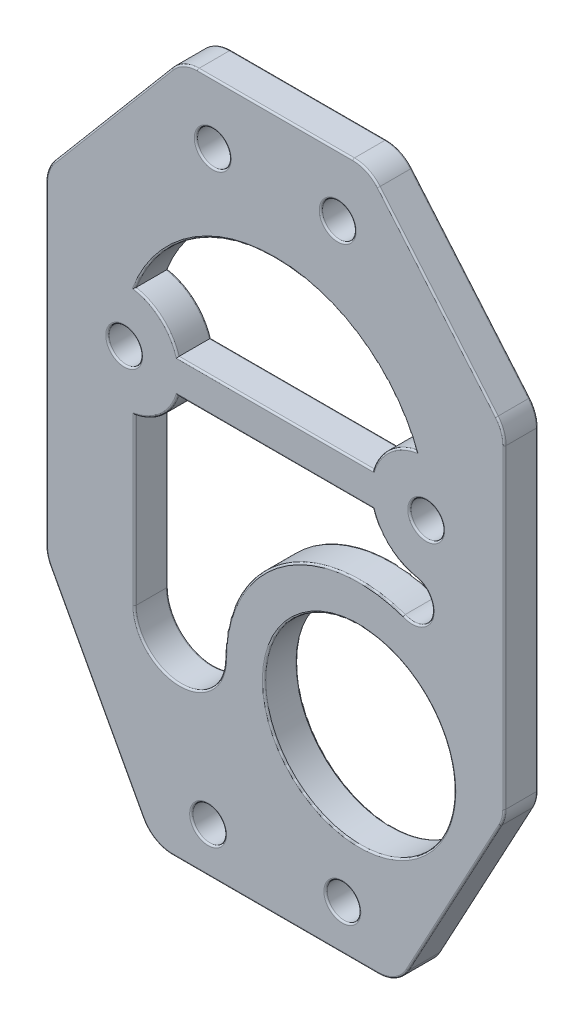
SolidWorks part; units mm, degrees
ref_plane "Front Plane" through (0, 0, 0) normal (0, 0, 1) x (1, 0, 0)
ref_plane "Top Plane" through (0, 0, 0) normal (0, 1, 0) x (1, 0, 0)
ref_plane "Right Plane" through (0, 0, 0) normal (1, 0, 0) x (0, 0, -1)
sketch "Sketch1" plane through (0, 0, 0) normal (0, 0, 1) x (1, 0, 0)
  line L0 (0, 0) -> (0, 62) construction
  line L1 (11, 0) -> (-11, 0)
  line L2 (-11, 0) -> (-20.5, 17.5997)
  line L3 (-20.5, 17.5997) -> (-20.5, 47.5997)
  line L4 (-20.5, 47.5997) -> (-8.3364, 62)
  line L5 (-8.3364, 62) -> (8.3364, 62)
  line L6 (20.5, 47.5997) -> (8.3364, 62)
  line L7 (20.5, 17.5997) -> (20.5, 47.5997)
  line L8 (11, 0) -> (20.5, 17.5997)
  line L9 (13.5, 37.2997) -> (-13.5, 37.2997) construction
  line L10 (-8.7303, 38.7997) -> (8.7303, 38.7997)
  line L11 (8.7303, 35.7997) -> (-8.7303, 35.7997) construction
  line L12 (8.7303, 35.7997) -> (8.7303, 38.7997) construction
  line L13 (8.7303, 38.7997) -> (-8.7303, 38.7997) construction
  line L14 (-8.7303, 35.7997) -> (-8.7303, 38.7997) construction
  line L15 (8.7303, 35.7997) -> (-8.7303, 38.7997) construction
  line L16 (8.7303, 38.7997) -> (-8.7303, 35.7997) construction
  line L17 (-8.7303, 35.7997) -> (8.7303, 35.7997)
  line L18 (13.5, 37.2997) -> (11.4846, 28.9188) construction
  line L19 (-12.5741, 32.3862) -> (-12.5741, 17.5997)
  circle A0 centre (-5.5864, 56.5294) radius 1.5
  circle A1 centre (-13.5, 37.2997) radius 1.5
  circle A2 centre (-6, 4) radius 1.5
  circle A3 centre (5.5864, 56.5294) radius 1.5
  circle A4 centre (6, 4) radius 1.5
  circle A5 centre (13.5, 37.2997) radius 1.5
  circle A6 centre (7.5, 17.5997) radius 8.5
  circle A7 centre (13.5, 37.2997) radius 5 construction
  circle A8 centre (-13.5, 37.2997) radius 5 construction
  circle A9 centre (7.5, 17.5997) radius 12 construction
  arc A10 (-12.5741, 42.2132) -> (12.5741, 42.2132) centre (0, 37.2997) cw
  arc A11 (-12.5741, 42.2132) -> (-8.7303, 38.7997) centre (-13.5, 37.2997) cw
  arc A12 (8.7303, 38.7997) -> (12.5741, 42.2132) centre (13.5, 37.2997) cw
  arc A13 (-8.7303, 35.7997) -> (-12.5741, 32.3862) centre (-13.5, 37.2997) cw
  arc A14 (8.7303, 35.7997) -> (12.5741, 32.3862) centre (13.5, 37.2997) ccw
  arc A15 (12.5741, 32.3862) -> (11.4846, 28.9188) centre (12.2352, 30.5879) cw
  arc A16 (11.4846, 28.9188) -> (-4.5, 17.5997) centre (7.5, 17.5997) ccw
  arc A17 (-12.5741, 17.5997) -> (-4.5, 17.5997) centre (-8.537, 17.5997) ccw
  dimension "D2" = 3
  dimension "D3" = 6
  dimension "D10" = 2.75
  dimension "D14" = 17
  dimension "D19" = 13.5
  dimension "D21" = 1.83
  dimension "D1" = 62
  dimension "D4" = 4
  dimension "D5" = 11
  dimension "D6" = 20
  dimension "D7" = 30
  dimension "D8" = 7
  dimension "D9" = 10.3
  dimension "D11" = 5.4706
  dimension "D12" = 18.85
  dimension "D13" = 20.5
  dimension "D15" = 13
  dimension "D20" = 3
  dimension "D16" = 3.5
  dimension "D17" = 3.5
  dimension "D18" = 3.5
extrude "Boss-Extrude1" add sketch "Sketch1" along normal mid plane 3
fillet "Fillet1" radius 3 8 edges at (-11, 0, 0) (-20.5, 17.5997, 0) (-20.5, 47.5997, 0) (-8.3364, 62, 0) (8.3364, 62, 0) (20.5, 47.5997, 0) (20.5, 17.5997, 0) (11, 0, 0)
fillet "Fillet2" radius 0.15 68 edges at (0.5652, 27.393, -1.5) (-8.537, 13.5627, -1.5) (-12.5741, 24.993, -1.5) (-10.1799, 33.5611, -1.5) (0, 35.7997, -1.5) (10.1799, 33.5611, -1.5) (13.981, 30.0393, -1.5) (16, 17.5997, -1.5) (4.5, 4, -1.5) (10.1799, 41.0383, -1.5) (0, 38.7997, -1.5) (-10.1799, 41.0383, -1.5) (0, 50.7997, -1.5) (-4.5, 4, -1.5) (-4.0864, 56.5294, -1.5) (10.7472, 0.4237, -1.5) (15.9951, 9.2539, -1.5) (20.4086, 17.6228, -1.5) (20.5, 32.43, -1.5) (20.3174, 47.5329, -1.5) (14.5135, 54.687, -1.5) (8.2068, 61.721, -1.5) (0, 62, -1.5) (-8.2068, 61.721, -1.5) (-14.5135, 54.687, -1.5) (-20.3174, 47.5329, -1.5) (-20.5, 32.43, -1.5) (-20.4086, 17.6228, -1.5) (-15.9951, 9.2539, -1.5) (-10.7472, 0.4237, -1.5) (0, 0, -1.5) (-12, 37.2997, -1.5) (4.0864, 56.5294, -1.5) (12, 37.2997, -1.5) (0, 35.7997, 1.5) (-10.1799, 33.5611, 1.5) (-12.5741, 24.993, 1.5) (-8.537, 13.5627, 1.5) (0.5652, 27.393, 1.5) (13.981, 30.0393, 1.5) (10.1799, 33.5611, 1.5) (-4.5, 4, 1.5) (-12, 37.2997, 1.5) (-4.0864, 56.5294, 1.5) (-20.4086, 17.6228, 1.5) (-20.5, 32.43, 1.5) (-20.3174, 47.5329, 1.5) (-14.5135, 54.687, 1.5) (-8.2068, 61.721, 1.5) (0, 62, 1.5) (8.2068, 61.721, 1.5) (14.5135, 54.687, 1.5) (20.3174, 47.5329, 1.5) (20.5, 32.43, 1.5) (20.4086, 17.6228, 1.5) (15.9951, 9.2539, 1.5) (10.7472, 0.4237, 1.5) (0, 0, 1.5) (-10.7472, 0.4237, 1.5) (-15.9951, 9.2539, 1.5) (0, 38.7997, 1.5) (10.1799, 41.0383, 1.5) (0, 50.7997, 1.5) (-10.1799, 41.0383, 1.5) (4.0864, 56.5294, 1.5) (4.5, 4, 1.5) (12, 37.2997, 1.5) (16, 17.5997, 1.5)
